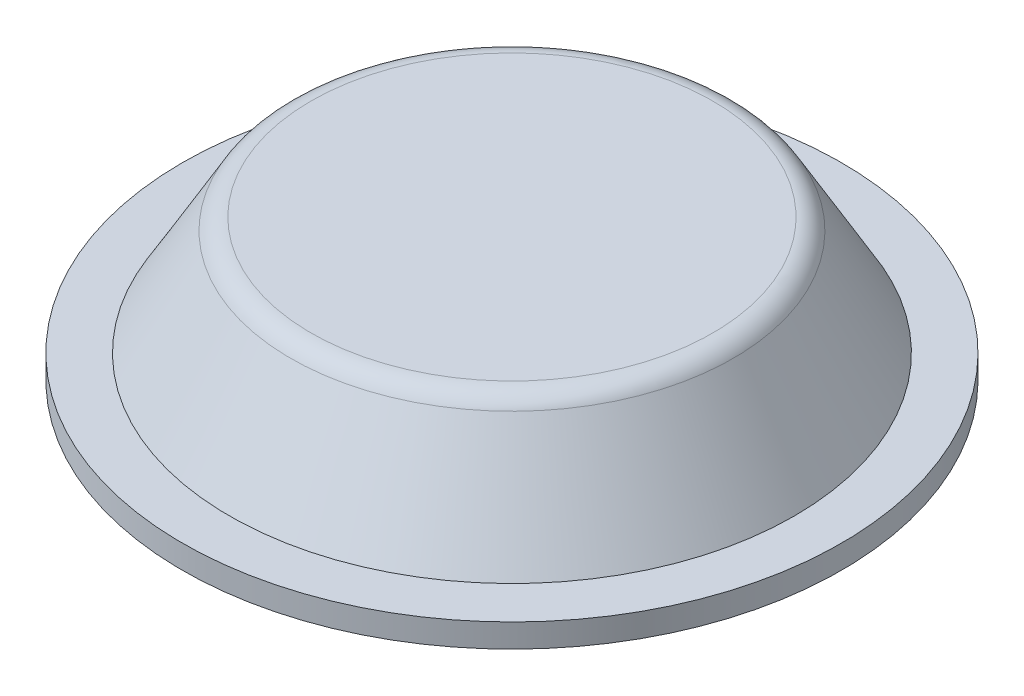
SolidWorks part; units mm, degrees
ref_plane "Front Plane" through (0, 0, 0) normal (0, 0, 1) x (1, 0, 0)
ref_plane "Top Plane" through (0, 0, 0) normal (0, 1, 0) x (1, 0, 0)
ref_plane "Right Plane" through (0, 0, 0) normal (1, 0, 0) x (0, 0, -1)
sketch "Sketch1" plane through (0, 0, 0) normal (0, 0, 1) x (1, 0, 0)
  line L0 (-35.56, 0) -> (-35.56, 2.54)
  line L1 (-35.56, 2.54) -> (-30.48, 2.54)
  line L3 (-29.0135, 0) -> (-35.56, 0)
  line L4 (0, 3.81) -> (-2.54, 3.81)
  line L7 (0, 3.81) -> (0, 0) construction
  line L8 (-21.6812, 15.24) -> (0, 15.24)
  line L9 (0, 15.24) -> (0, 3.81)
  line L10 (-2.54, 3.81) -> (-2.54, 12.7)
  line L11 (-2.54, 12.7) -> (-21.6812, 12.7)
  line L12 (-30.48, 2.54) -> (-23.8809, 13.97)
  line L13 (-29.0135, 0) -> (-21.6812, 12.7)
  arc A3 (-23.8809, 13.97) -> (-21.6812, 15.24) centre (-21.6812, 12.7) cw
  point P2 (-19.7128, 11.43)
  point P4 (-29.1537, 0)
  point P8 (-28.9722, 0)
  dimension "D7" = 2.54
  dimension "D6" = 2.54
  dimension "D1" = 2.54
  dimension "D2" = 35.56
  dimension "D3" = 5.08
  dimension "D4" = 60
  dimension "D5" = 2.54
  dimension "D8" = 15.24
  dimension "D9" = 2.54
  dimension "D10" = 8.89
revolve "Revolve1" add sketch "Sketch1" angle 360 about L9
